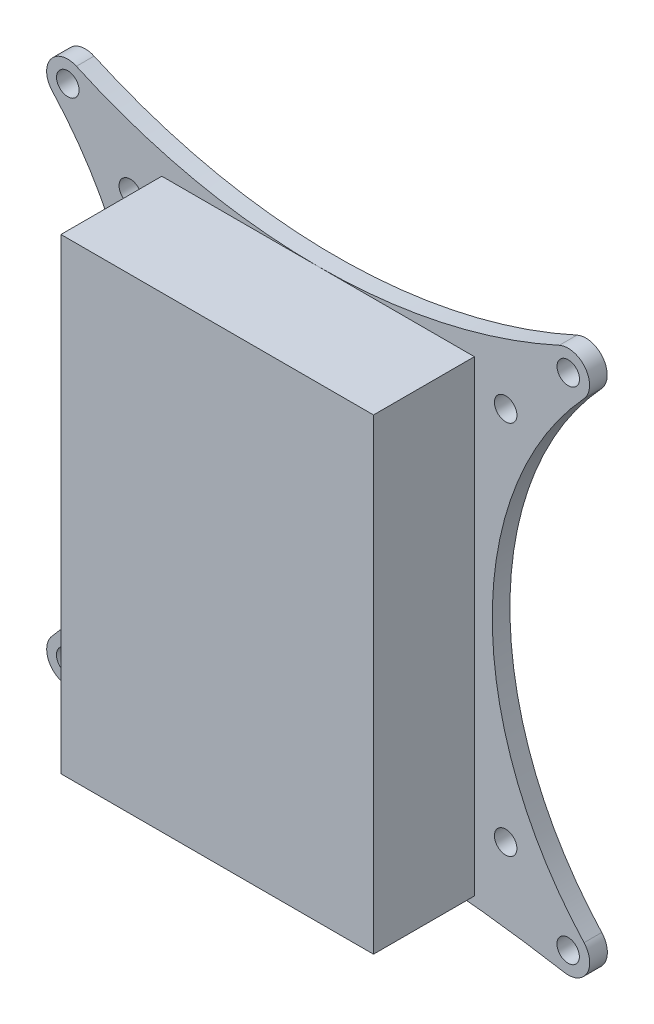
SolidWorks part; units mm, degrees
ref_plane "Front Plane" through (0, 0, 0) normal (0, 0, 1) x (1, 0, 0)
ref_plane "Top Plane" through (0, 0, 0) normal (0, 1, 0) x (1, 0, 0)
ref_plane "Right Plane" through (0, 0, 0) normal (1, 0, 0) x (0, 0, -1)
sketch "Sketch1" plane through (0, 0, 0) normal (0, 0, 1) x (1, 0, 0)
  circle A0 centre (103434.8212, 103424.1326) radius 2228.8484
  circle A2 centre (4216.1999, 103431.9314) radius 2232.5151
  circle A3 centre (4214.8751, 4248.8491) radius 2255.3836
  circle A4 centre (103411.0284, 4238.8666) radius 2221.1942
  circle A5 centre (91025.9698, 16629.5761) radius 2229.2646
  circle A6 centre (16598.1709, 16611.1645) radius 2222.1533
  circle A7 centre (16610.1095, 91032.5338) radius 2227.9623
  circle A8 centre (91028.833, 91029.0452) radius 2234.3286
  arc A9 (106545.0799, 100518.4368) -> (101661.5488, 107248.8243) centre (103419.3256, 103387.3322) ccw
  arc A10 (5922.9563, 107283.3564) -> (1110.3677, 100672.1886) centre (4191.3544, 103486.6313) ccw
  arc A11 (1130.5182, 7078.7507) -> (4967.6874, 75.797) centre (4247.4791, 4233.9071) ccw
  arc A12 (102711.6764, 65.3942) -> (106569.5434, 7132.1006) centre (103438.2803, 4255.125) ccw
  arc A13 (106545.0799, 100518.4368) -> (106569.5434, 7132.1006) centre (157404.283, 53838.5886) ccw
  arc A14 (1130.5182, 7078.7507) -> (1110.3677, 100672.1886) centre (-50130.3491, 53864.4355) ccw
  arc A15 (5922.9563, 107283.3564) -> (101661.5488, 107248.8243) centre (53830.1464, 212325.0678) ccw
  arc A16 (102711.6764, 65.3942) -> (4967.6874, 75.797) centre (53809.6708, -281912.5235) ccw
  point P20 (53788.5044, 96874.3932)
  point P22 (53840.1293, 4274.3932)
  dimension "D1" = 92600
extrude "Boss-Extrude1" add sketch "Sketch1" along normal blind 3500
sketch "Sketch2" plane through (0, 0, 3500) normal (0, 0, 1) x (1, 0, 0)
  line L1 (84824.3522, 4274.3932) -> (22855.9065, 4274.3932)
  line L2 (84824.3522, 4274.3932) -> (84824.3522, 96874.3932)
  line L3 (84824.3522, 96874.3932) -> (22855.9065, 96874.3932)
  line L4 (22855.9065, 4274.3932) -> (22855.9065, 96874.3932)
  arc A0 (5922.9563, 107283.3564) -> (101661.5488, 107248.8243) centre (53830.1464, 212325.0678) ccw construction
  arc A1 (102711.6764, 65.3942) -> (4967.6874, 75.797) centre (53809.6708, -281912.5235) ccw construction
  point P7 (53788.5044, 96874.3932)
  point P11 (53840.1293, 4274.3932)
  point P12 (53840.1293, 4274.3932)
extrude "Boss-Extrude2" add sketch "Sketch2" along normal blind 20000
scale "Scale1" scale about centroid uniform scaling yes scale factor 0.001
